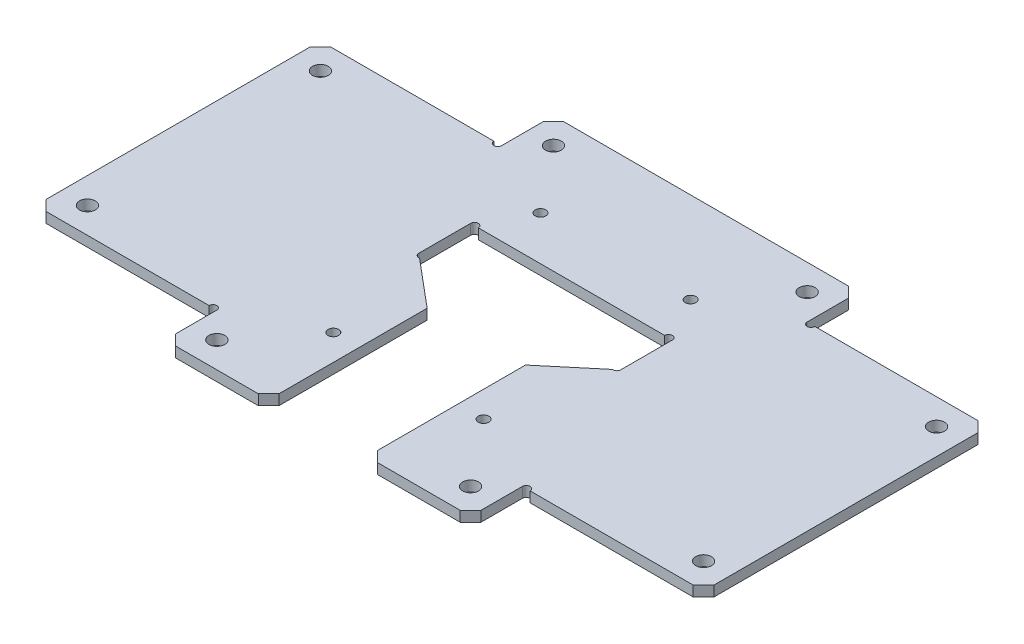
SolidWorks part; units mm, degrees
ref_plane "前视基准面" through (0, 0, 0) normal (0, 0, 1) x (1, 0, 0)
ref_plane "上视基准面" through (0, 0, 0) normal (0, 1, 0) x (1, 0, 0)
ref_plane "右视基准面" through (0, 0, 0) normal (1, 0, 0) x (0, 0, -1)
sketch "草图1" plane through (0, 0, 0) normal (0, 1, 0) x (1, 0, 0)
  line L0 (59, 52) -> (-59, 52)
  line L1 (-59, 52) -> (-59, 32)
  line L2 (-59, 32) -> (-129, 32)
  line L3 (-129, 32) -> (-129, -78)
  line L4 (-129, -78) -> (-59, -78)
  line L5 (-59, -78) -> (-59, -98)
  line L6 (0, 0) -> (0, 52) construction
  line L7 (-59, -98) -> (-19, -98)
  line L8 (-19, -98) -> (-19, 0)
  line L9 (-19, 0) -> (19, 0)
  line L10 (19, -98) -> (19, 0)
  line L11 (59, -98) -> (19, -98)
  line L12 (59, -78) -> (59, -98)
  line L13 (129, -78) -> (59, -78)
  line L14 (129, 32) -> (129, -78)
  line L15 (59, 32) -> (129, 32)
  line L16 (59, 52) -> (59, 32)
  circle A0 centre (-49, 42) radius 3.05
  circle A1 centre (-119, 22) radius 3.05
  circle A2 centre (-119, -68) radius 3.05
  circle A3 centre (-49, -88) radius 3.05
  circle A4 centre (49, -88) radius 3.05
  circle A5 centre (119, -68) radius 3.05
  circle A6 centre (119, 22) radius 3.05
  circle A7 centre (49, 42) radius 3.05
  dimension "D7" = 6.1
  dimension "D8" = 10
  dimension "D9" = 10
  dimension "D10" = 10
  dimension "D11" = 10
  dimension "D12" = 10
  dimension "D13" = 10
  dimension "D14" = 10
  dimension "D1" = 110
  dimension "D2" = 150
  dimension "D3" = 70
  dimension "D4" = 40
  dimension "D5" = 38
  dimension "D6" = 52
extrude "凸台-拉伸1" add sketch "草图1" along normal mid plane 4
sketch "草图2" plane through (0, 2, 0) normal (0, 1, 0) x (1, 0, 0)
  line L0 (-19, 0) -> (-39, 0)
  line L1 (-39, 0) -> (-39, -20)
  line L2 (-39, -20) -> (-19, -36.782)
  line L3 (-19, -98) -> (-19, 0) construction
  line L4 (-19, -36.782) -> (-19, 0)
  line L5 (0, 0) -> (0, 52) construction
  line L6 (59, 52) -> (-59, 52) construction
  line L7 (39, -20) -> (19, -36.782)
  line L8 (39, 0) -> (39, -20)
  line L9 (19, 0) -> (39, 0)
  line L10 (19, -36.782) -> (19, 0)
  dimension "D1" = 20
  dimension "D2" = 20
  dimension "D3" = 50
extrude "切除-拉伸1" cut sketch "草图2" against normal through all
sketch "草图3" plane through (0, 2, 0) normal (0, 1, 0) x (1, 0, 0)
  line L0 (-39, 0) -> (39, 0) construction
  line L2 (-39, 0) -> (-39, -20) construction
  line L3 (39, -20) -> (39, 0) construction
  line L4 (-59, 32) -> (-129, 32) construction
  line L5 (-129, -78) -> (-59, -78) construction
  line L6 (59, -78) -> (129, -78) construction
  line L7 (129, 32) -> (59, 32) construction
  circle A0 centre (-37.5, 0) radius 1.5
  circle A1 centre (-37.5, -20) radius 1.5
  circle A2 centre (37.5, -20) radius 1.5
  circle A3 centre (37.5, 0) radius 1.5
  circle A4 centre (-60.5, 32) radius 1.5
  circle A5 centre (-60.5, -78) radius 1.5
  circle A6 centre (60.5, -78) radius 1.5
  circle A7 centre (60.5, 32) radius 1.5
  dimension "D1" = 3
extrude "切除-拉伸2" cut sketch "草图3" against normal through all
sketch "草图4" plane through (0, 2, 0) normal (0, 1, 0) x (1, 0, 0)
  line L0 (-19, -98) -> (-19, -36.782) construction
  line L1 (29, 17) -> (-29, 17) construction
  line L2 (29, 17) -> (29, -63) construction
  line L3 (29, -63) -> (-29, -63) construction
  line L4 (-29, 17) -> (-29, -63) construction
  line L5 (29, 17) -> (-29, -63) construction
  line L6 (29, -63) -> (-29, 17) construction
  circle A2 centre (-29, -63) radius 2.05
  circle A5 centre (29, -63) radius 2.05
  circle A6 centre (29, 17) radius 2.05
  circle A7 centre (-29, 17) radius 2.05
  circle A8 centre (-49, 42) radius 3.05 construction
  circle A9 centre (-49, -88) radius 3.05 construction
  point P0 (0, -23)
  dimension "D1" = 4.1
  dimension "D2" = 10
  dimension "D3" = 25
  dimension "D4" = 25
extrude "切除-拉伸3" cut sketch "草图4" against normal through all
chamfer "倒角1" distance 4 angle 45 10 edges at (19, 0, 98) (-19, 0, 98) (-129, 0, 78) (-59, 0, 98) (59, 0, 98) (129, 0, 78) (129, 0, -32) (59, 0, -52) (-129, 0, -32) (-59, 0, -52)
